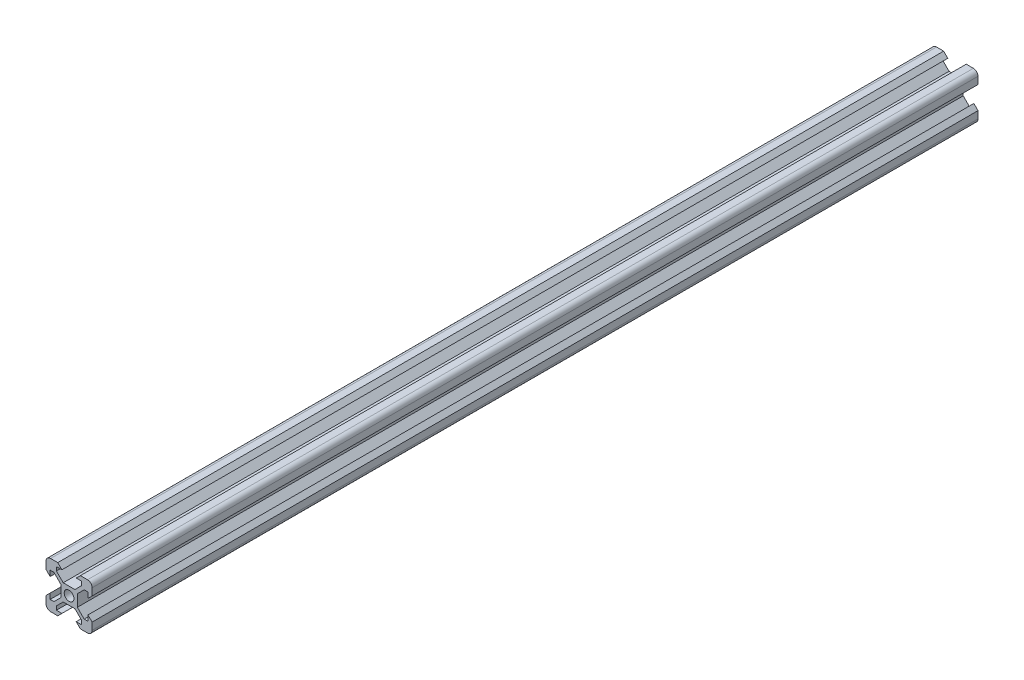
SolidWorks part; units mm, degrees
material "6061 Alloy"
ref_plane "Front Plane" through (0, 0, 0) normal (0, 0, 1) x (1, 0, 0)
ref_plane "Top Plane" through (0, 0, 0) normal (0, 1, 0) x (1, 0, 0)
ref_plane "Right Plane" through (0, 0, 0) normal (1, 0, 0) x (0, 0, -1)
sketch "Sketch1" plane through (0, 0, 0) normal (0, 0, 1) x (1, 0, 0)
  line L0 (-4.9, -10) -> (-5.5, -10)
  line L1 (-10, -10) -> (10, -10) construction
  line L2 (-10, -10) -> (-10, 10) construction
  line L3 (-10, 10) -> (10, 10) construction
  line L4 (10, -10) -> (10, 10) construction
  line L5 (-10, -10) -> (10, 10) construction
  line L6 (-10, 10) -> (10, -10) construction
  line L7 (-3.6, 3.6) -> (3.6, 3.6)
  line L8 (-3.6, 3.6) -> (-3.6, -3.6)
  line L9 (-3.6, -3.6) -> (3.6, -3.6)
  line L10 (3.6, 3.6) -> (3.6, -3.6)
  line L11 (-8, 10) -> (-5.5, 10)
  line L12 (-10, 8) -> (-10, 5.5)
  line L13 (-10, 5.5) -> (-5.5, 5.5)
  line L14 (-5.5, 10) -> (-5.5, 5.5)
  line L15 (8, 10) -> (5.5, 10)
  line L16 (10, 8) -> (10, 5.5)
  line L17 (10, 5.5) -> (5.5, 5.5)
  line L18 (5.5, 10) -> (5.5, 5.5)
  line L19 (8, -10) -> (5.5, -10)
  line L20 (10, -8) -> (10, -5.5)
  line L21 (10, -5.5) -> (5.5, -5.5)
  line L22 (5.5, -10) -> (5.5, -5.5)
  line L23 (-8, -10) -> (-5.5, -10)
  line L24 (-10, -8) -> (-10, -5.5)
  line L25 (-10, -5.5) -> (-5.5, -5.5)
  line L26 (-5.5, -10) -> (-5.5, -5.5)
  line L27 (-3.1, -8.2) -> (-4.9, -10)
  line L28 (-3.1, -8.2) -> (-5.5, -8.2)
  line L29 (4.9, -10) -> (5.5, -10)
  line L30 (3.1, -8.2) -> (4.9, -10)
  line L31 (3.1, -8.2) -> (5.5, -8.2)
  line L32 (-4.9, 10) -> (-5.5, 10)
  line L33 (-3.1, 8.2) -> (-4.9, 10)
  line L34 (-3.1, 8.2) -> (-5.5, 8.2)
  line L35 (4.9, 10) -> (5.5, 10)
  line L36 (0, 0) -> (17.4618, 0) construction
  line L37 (3.1, 8.2) -> (4.9, 10)
  line L38 (3.1, 8.2) -> (5.5, 8.2)
  line L39 (8.2, 3.1) -> (8.2, 5.5)
  line L40 (8.2, 3.1) -> (10, 4.9)
  line L41 (10, 4.9) -> (10, 5.5)
  line L42 (10, -4.9) -> (10, -5.5)
  line L43 (8.2, -3.1) -> (10, -4.9)
  line L44 (8.2, -3.1) -> (8.2, -5.5)
  line L57 (-8.2, -3.1) -> (-10, -4.9)
  line L58 (-10, -4.9) -> (-10, -5.5)
  line L61 (-8.2, -3.1) -> (-8.2, -5.5)
  line L62 (-8.2, 3.1) -> (-10, 4.9)
  line L63 (-10, 4.9) -> (-10, 5.5)
  line L66 (-8.2, 3.1) -> (-8.2, 5.5)
  line L67 (-2.7729, 2.7729) -> (-6.4508, 6.4508) construction
  line L68 (-2.2426, 3.3033) -> (-5.9205, 6.9812)
  line L69 (-3.3033, 2.2426) -> (-6.9812, 5.9205)
  line L70 (6.7372, 6.7372) -> (2.7729, 2.7729)
  line L71 (6.309, -6.309) -> (2.7729, -2.7729)
  line L72 (-2.8687, -2.8687) -> (-6.5971, -6.5971)
  line L73 (6.2069, 7.2675) -> (2.2426, 3.3033)
  line L74 (6.8393, -5.7786) -> (3.3033, -2.2426)
  line L75 (-3.399, -2.3384) -> (-7.1274, -6.0667)
  line L76 (7.2675, 6.2069) -> (3.3033, 2.2426)
  line L77 (5.7786, -6.8393) -> (2.2426, -3.3033)
  line L78 (-2.3384, -3.399) -> (-6.0667, -7.1274)
  circle A0 centre (0, 0) radius 2.1
  arc A1 (-8, -10) -> (-10, -8) centre (-8, -8) cw
  arc A2 (8, -10) -> (10, -8) centre (8, -8) ccw
  arc A3 (8, 10) -> (10, 8) centre (8, 8) cw
  arc A4 (-8, 10) -> (-10, 8) centre (-8, 8) ccw
  point P0 (0, 0)
  dimension "D3" = 4.2
  dimension "D12" = 2
  dimension "D1" = 20
  dimension "D4" = 6.4
  dimension "D5" = 6.4
  dimension "D6" = 6.4
  dimension "D7" = 6.4
  dimension "D8" = 4.5
  dimension "D9" = 4.5
  dimension "D10" = 4.5
  dimension "D11" = 4.5
  dimension "D13" = 45
  dimension "D19" = 45
  dimension "D20" = 6.2
  dimension "D23" = 1.8
  dimension "D24" = 1.8
  dimension "D28" = 0.75
  dimension "D26" = 0.75
  dimension "D27" = 0.75
  dimension "D29" = 0.75
extrude "Boss-Extrude1" add sketch "Sketch1" along normal blind 384.175
